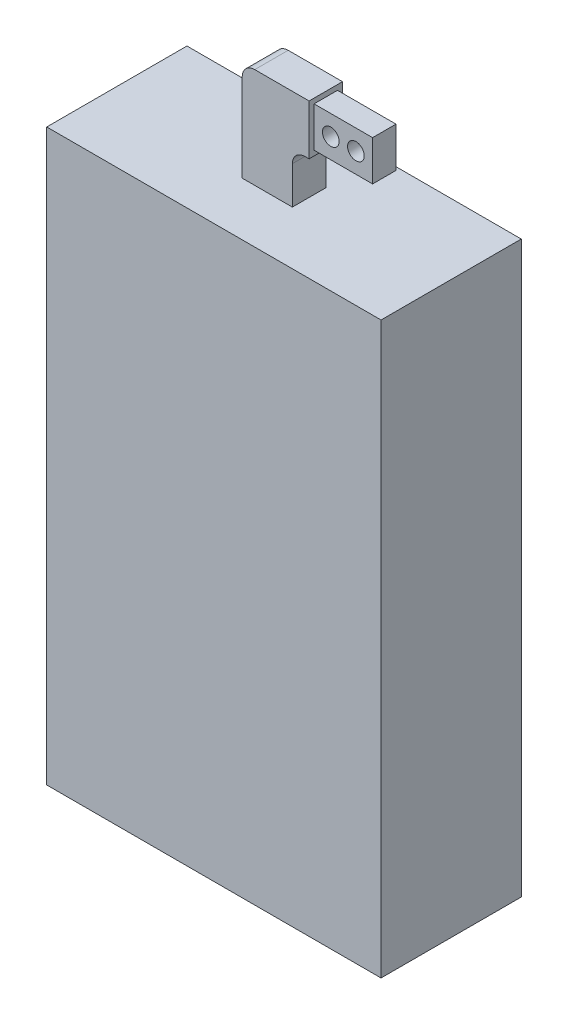
SolidWorks part; units mm, degrees
ref_plane "Front Plane" through (0, 0, 0) normal (0, 0, 1) x (1, 0, 0)
ref_plane "Top Plane" through (0, 0, 0) normal (0, 1, 0) x (1, 0, 0)
ref_plane "Right Plane" through (0, 0, 0) normal (1, 0, 0) x (0, 0, -1)
sketch "Sketch1" plane through (0, 0, 0) normal (0, 1, 0) x (1, 0, 0)
  line L1 (100, -41.945) -> (-100, -41.945)
  line L2 (100, -41.945) -> (100, 41.945)
  line L3 (100, 41.945) -> (-100, 41.945)
  line L4 (-100, -41.945) -> (-100, 41.945)
  line L5 (100, -41.945) -> (-100, 41.945) construction
  line L6 (100, 41.945) -> (-100, -41.945) construction
  point P0 (0, 0)
  dimension "D1" = 200
  dimension "D2" = 83.89
extrude "Wheel & Steering Dummy" add sketch "Sketch1" against normal blind 340.92
sketch "Sketch2" plane through (0, 0, 0) normal (0, 0, 1) x (1, 0, 0)
  line L0 (-100, 0) -> (100, 0) construction
  line L1 (-15, 0) -> (15, 0)
  line L2 (-15, 0) -> (-15, 60)
  line L3 (-15, 60) -> (15, 60)
  line L4 (15, 0) -> (15, 30)
  line L6 (15, 60) -> (60, 60)
  line L8 (15, 30) -> (60, 30)
  line L9 (60, 60) -> (60, 30)
  dimension "D1" = 30
  dimension "D2" = 15
  dimension "D3" = 60
  dimension "D4" = 45
  dimension "D5" = 30
  dimension "D6" = 15
extrude "Mount Body" add sketch "Sketch2" along normal blind 10 and the other way blind 10
sketch "Sketch3" plane through (60, 0, 0) normal (1, 0, 0) x (0, 0, -1)
  line L1 (-10, 60) -> (10, 60)
  line L2 (-10, 60) -> (-10, 30)
  line L3 (-10, 30) -> (10, 30)
  line L4 (10, 60) -> (10, 30)
  line L5 (7, 33) -> (-7, 33)
  line L6 (7, 33) -> (7, 57)
  line L7 (7, 57) -> (-7, 57)
  line L8 (-7, 33) -> (-7, 57)
  line L9 (7, 33) -> (-7, 57) construction
  line L10 (7, 57) -> (-7, 33) construction
  point P6 (0, 45)
  dimension "D1" = 3
  dimension "D2" = 3
  dimension "D3" = 3
  dimension "D4" = 3
extrude "Mount Tongue" cut sketch "Sketch3" against normal blind 35
sketch "Sketch4" plane through (0, 0, 7) normal (0, 0, 1) x (1, 0, 0)
  line L0 (60, 45) -> (25, 45) construction
  line L1 (60, 57) -> (60, 33) construction
  line L2 (25, 57) -> (25, 33) construction
  circle A0 centre (35, 45) radius 5
  circle A1 centre (50, 45) radius 5
  dimension "D1" = 10
  dimension "D2" = 10
  dimension "D3" = 10
  dimension "D4" = 10
extrude "Mount Bolt Holes" cut sketch "Sketch4" against normal through all
fillet "Fillet1" radius 7.5 2 edges at (-15, 60, 0) (15, 30, 0)
equation "\"neck_height\"= 30.0mm"
equation "\"arm_length\"= 45.0mm"
equation "\"angle\"= 0"
equation "\"width\"= 30.0mm"
equation "\"mount_thickness\"= 20.0mm"
equation "\"fillet_radius\"= 7.5mm"
equation "\"linkage_mount_tongue_length\"= 35.0mm"
equation "\"linkage_mount_shoulder_depth\"= 3.0mm"
equation "\"linkage_mount_bolt_diameter\"= 10.0mm"
equation "\"linkage_mount_bolt_spacing\"= 5.0mm"
equation "\"D1@Sketch2\"=\"width\""
equation "\"D2@Sketch2\"=\"width\"/2"
equation "\"D3@Sketch2\"=\"neck_height\"+\"width\""
equation "\"D4@Sketch2\"=\"arm_length\""
equation "\"D5@Sketch2\"=\"width\""
equation "\"D6@Sketch2\"=\"width\"/2"
equation "\"D1@Mount Body\" = \"mount_thickness\" / 2"
equation "\"D2@Mount Body\"=\"mount_thickness\"/2"
equation "\"D1@Sketch3\"=\"linkage_mount_shoulder_depth\""
equation "\"D2@Sketch3\"=\"linkage_mount_shoulder_depth\""
equation "\"D4@Sketch3\"=\"linkage_mount_shoulder_depth\""
equation "\"D3@Sketch3\"=\"linkage_mount_shoulder_depth\""
equation "\"D1@Mount Tongue\"=\"linkage_mount_tongue_length\""
equation "\"D1@Sketch4\"=\"linkage_mount_bolt_diameter\""
equation "\"D2@Sketch4\"=\"linkage_mount_bolt_diameter\""
equation "\"D3@Sketch4\"=\"linkage_mount_bolt_spacing\"+\"linkage_mount_bolt_diameter\"/2"
equation "\"D4@Sketch4\"=\"linkage_mount_bolt_spacing\"+\"linkage_mount_bolt_diameter\"/2"
equation "\"D1@Fillet1\"=\"fillet_radius\""
